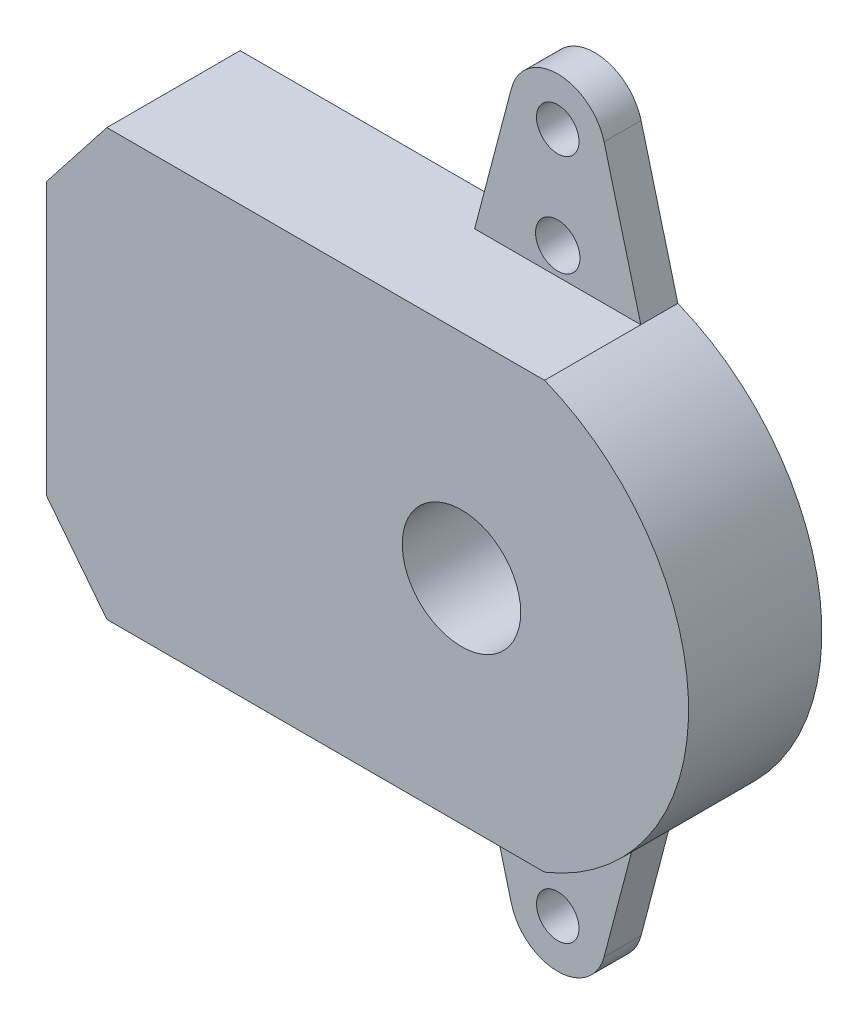
SolidWorks part; units mm, degrees
ref_plane "Plan de face" through (0, 0, 0) normal (0, 0, 1) x (1, 0, 0)
ref_plane "Plan de dessus" through (0, 0, 0) normal (0, 1, 0) x (1, 0, 0)
ref_plane "Plan de droite" through (0, 0, 0) normal (1, 0, 0) x (0, 0, -1)
sketch "Esquisse1" plane through (0, 0, 0) normal (0, 0, 1) x (1, 0, 0)
  line L0 (4.0875, 28.77) -> (4.0875, 0) construction
  line L1 (0, 0) -> (43.38, 0) construction
  line L2 (0, 0) -> (0, 28.77) construction
  line L3 (0, 28.77) -> (43.38, 28.77) construction
  line L4 (43.38, 0) -> (43.38, 28.77) construction
  line L7 (22.4275, 0) -> (24.9086, -9.4497)
  line L8 (31.1714, -9.4497) -> (33.6525, 0)
  line L9 (0, 14.385) -> (43.38, 14.385) construction
  line L16 (22.4275, 28.77) -> (24.9086, 38.2197)
  line L17 (31.1714, 38.2197) -> (33.6525, 28.77)
  line L18 (22.4275, 28.77) -> (4.0875, 28.77)
  line L19 (4.0875, 28.77) -> (0, 23.555)
  line L20 (28.04, 37.3975) -> (28.04, -8.6275) construction
  line L21 (4.0875, 0) -> (22.4275, 0)
  line L22 (0, 23.555) -> (0, 5.215)
  line L23 (0, 5.215) -> (4.0875, 0)
  arc A0 (24.9086, 38.2197) -> (31.1714, 38.2197) centre (28.04, 37.3975) cw
  arc A1 (24.9086, -9.4497) -> (31.1714, -9.4497) centre (28.04, -8.6275) ccw
  circle A2 centre (28.04, 37.3975) radius 1.435
  circle A3 centre (28.04, -8.6275) radius 1.435
  arc A4 (33.6525, 0) -> (33.6525, 28.77) centre (27.88, 14.385) ccw
  circle A5 centre (28.04, 30.6) radius 1.5
  circle A6 centre (28.04, -1.83) radius 1.5
  point P15 (28.04, -11.865)
  point P16 (28.04, 40.635)
  dimension "D19" = 3
  dimension "D21" = 2.87
  dimension "D4" = 15.5
  dimension "D3" = 15.34
  dimension "D5" = 28.77
  dimension "D6" = 52.5
  dimension "D7" = 43.38
  dimension "D8" = 18.34
  dimension "D9" = 18.34
  dimension "D10" = 32.43
  dimension "D11" = 46.025
extrude "Boss.-Extru.2" add sketch "Esquisse1" along normal blind 2.5
sketch "Esquisse2" plane through (0, 0, 2.5) normal (0, 0, 1) x (1, 0, 0)
  line L0 (4.0875, 28.77) -> (33.6525, 28.77)
  line L1 (33.6525, 0) -> (4.0875, 0)
  line L2 (4.0875, 0) -> (0, 5.215)
  line L3 (0, 5.215) -> (0, 23.555)
  line L13 (4.0875, 28.77) -> (0, 23.555)
  line L14 (0, 23.555) -> (0, 5.215)
  line L15 (0, 5.215) -> (4.0875, 0)
  line L16 (4.0875, 0) -> (22.4275, 0)
  line L17 (22.4275, 0) -> (24.9086, -9.4497)
  line L18 (31.1714, -9.4497) -> (33.6525, 0)
  line L19 (33.6525, 28.77) -> (31.1714, 38.2197)
  line L20 (24.9086, 38.2197) -> (22.4275, 28.77)
  line L21 (22.4275, 28.77) -> (4.0875, 28.77)
  line L22 (4.0875, 28.77) -> (0, 23.555)
  arc A0 (33.6525, 28.77) -> (33.6525, 0) centre (27.88, 14.385) cw
  arc A1 (33.6525, 0) -> (33.6525, 28.77) centre (27.88, 14.385) ccw construction
  arc A5 (24.9086, -9.4497) -> (31.1714, -9.4497) centre (28.04, -8.6275) ccw
  arc A6 (33.6525, 0) -> (33.6525, 28.77) centre (27.88, 14.385) ccw
  arc A7 (31.1714, 38.2197) -> (24.9086, 38.2197) centre (28.04, 37.3975) ccw
  dimension "D1" = 0
extrude "Boss.-Extru.3" add sketch "Esquisse2" along normal blind 6.5
sketch "Esquisse3" plane through (0, 0, 9) normal (0, 0, 1) x (1, 0, 0)
  line L0 (28.04, 37.3975) -> (28.04, -8.6275) construction
  circle A0 centre (28.04, 14.385) radius 4
  point P5 (28.04, 14.385)
  dimension "D1" = 8
extrude "Enlèv. mat.-Extru.1" cut sketch "Esquisse3" against normal blind 10
